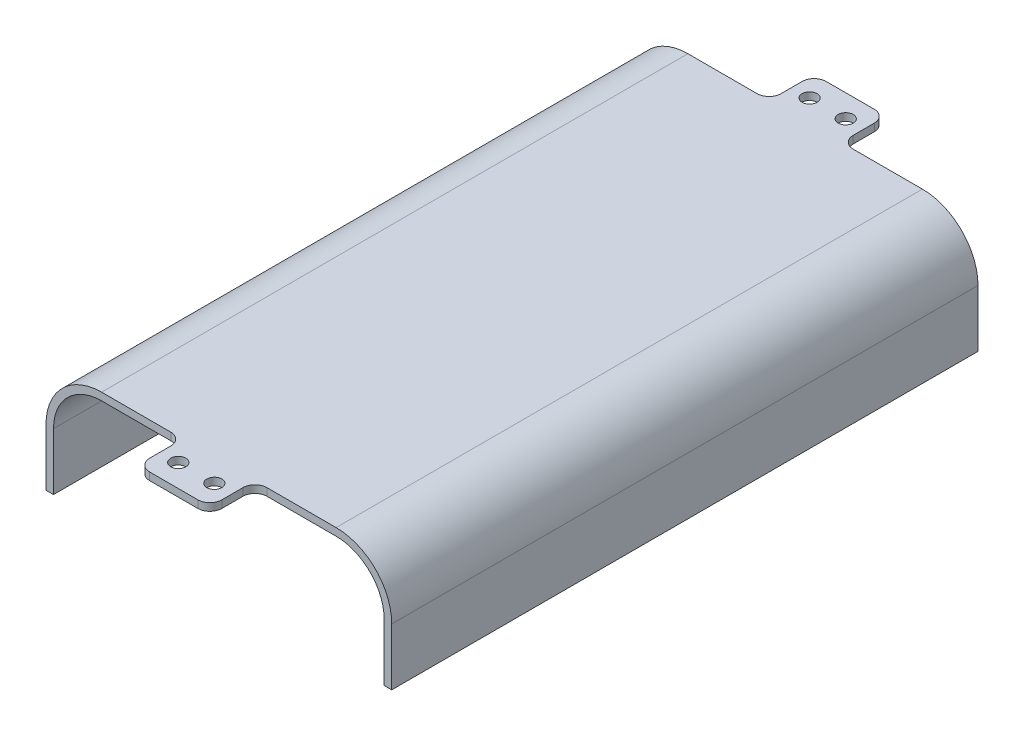
SolidWorks part; units mm, degrees
ref_plane "前视基准面" through (0, 0, 0) normal (0, 0, 1) x (1, 0, 0)
ref_plane "上视基准面" through (0, 0, 0) normal (0, 1, 0) x (1, 0, 0)
ref_plane "右视基准面" through (0, 0, 0) normal (1, 0, 0) x (0, 0, -1)
other "Configuration Table"
sketch "草图1" plane through (0, 0, 0) normal (0, 0, 1) x (1, 0, 0)
  line L1 (-39, 17.5) -> (39, 17.5)
  line L2 (-55, 1.5) -> (-55, -17.5)
  line L3 (-55, -17.5) -> (55, -17.5)
  line L4 (55, 1.5) -> (55, -17.5)
  arc A1 (-39, 17.5) -> (-55, 1.5) centre (-39, 1.5) ccw
  arc A2 (39, 17.5) -> (55, 1.5) centre (39, 1.5) cw
  point P0 (0, 0)
extrude "凸台-拉伸1" add sketch "草图1" along normal blind 225
shell "抽壳2" thickness 2.5
sketch "草图2" plane through (0, 20, 0) normal (0, 1, 0) x (1, 0, 0)
  line L1 (-8, 0) -> (-68.0332, 0)
  line L6 (-68.0332, 0) -> (-68.0332, -15)
  line L7 (-68.0332, -15) -> (-57.5, -15)
  line L9 (-12, -4) -> (-12, -11)
  line L10 (-16, -15) -> (-57.5, -15)
  line L11 (-57.5, -225) -> (-57.5, 0) construction
  line L15 (68.3162, -15) -> (68.3162, 0)
  line L16 (16, -15) -> (68.3162, -15)
  line L17 (12, -4) -> (12, -11)
  line L18 (8, 0) -> (68.3162, 0)
  line L28 (8, -225) -> (68.3162, -225)
  line L29 (12, -221) -> (12, -214)
  line L30 (16, -210) -> (68.3162, -210)
  line L31 (68.3162, -210) -> (68.3162, -225)
  line L32 (-16, -210) -> (-57.5, -210)
  line L33 (-12, -221) -> (-12, -214)
  line L34 (-68.0332, -210) -> (-57.5, -210)
  line L35 (-68.0332, -225) -> (-68.0332, -210)
  line L37 (-8, -225) -> (-68.0332, -225)
  circle A0 centre (-6, -7.5) radius 2.5
  circle A1 centre (6, -7.5) radius 2.5
  arc A2 (-12, -11) -> (-16, -15) centre (-16, -11) cw
  arc A3 (-12, -4) -> (-8, 0) centre (-8, -4) cw
  arc A4 (12, -4) -> (8, 0) centre (8, -4) ccw
  arc A5 (16, -15) -> (12, -11) centre (16, -11) cw
  arc A12 (16, -210) -> (12, -214) centre (16, -214) ccw
  arc A13 (12, -221) -> (8, -225) centre (8, -221) cw
  arc A14 (-12, -221) -> (-8, -225) centre (-8, -221) ccw
  arc A15 (-12, -214) -> (-16, -210) centre (-16, -214) ccw
  circle A16 centre (6, -217.5) radius 2.5
  circle A17 centre (-6, -217.5) radius 2.5
  point P28 (-12, -15)
  point P37 (12, -15)
  point P57 (12, -210)
  point P58 (-12, -210)
  dimension "D1" = 4
  dimension "D2" = 4
  dimension "D3" = 4
  dimension "D4" = 4
extrude "切除-拉伸1" cut sketch "草图2" against normal through all
